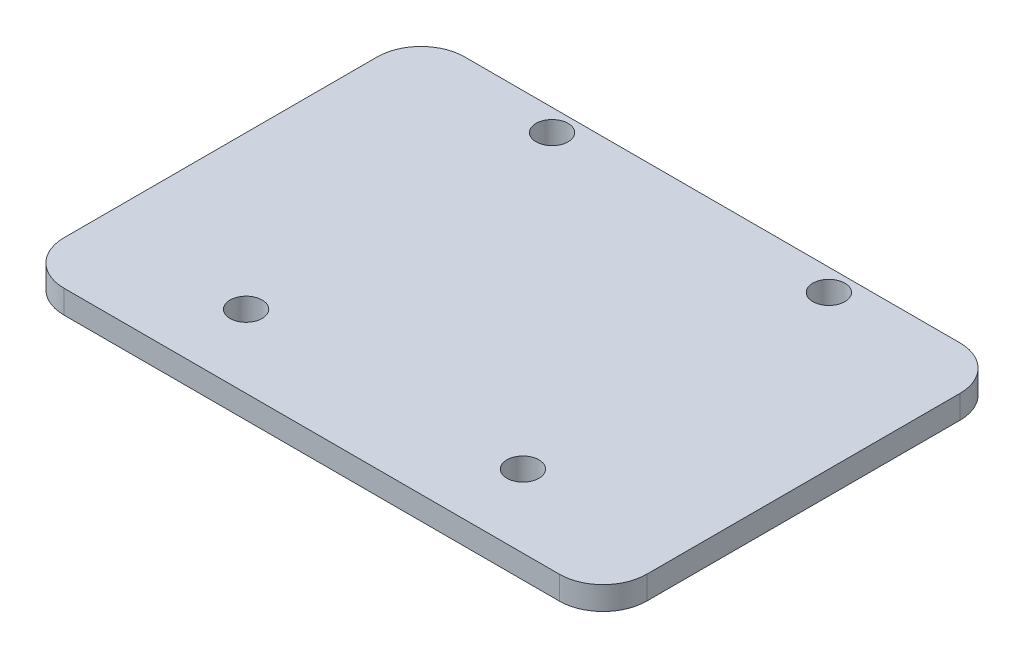
SolidWorks part; units mm, degrees
ref_plane "Front Plane" through (0, 0, 0) normal (0, 0, 1) x (1, 0, 0)
ref_plane "Top Plane" through (0, 0, 0) normal (0, 1, 0) x (1, 0, 0)
ref_plane "Right Plane" through (0, 0, 0) normal (1, 0, 0) x (0, 0, -1)
sketch "Sketch1" plane through (0, 0, 0) normal (0, 1, 0) x (1, 0, 0)
  line L0 (-20, 13.75) -> (20, -13.75) construction
  line L1 (-20, 13.75) -> (20, 13.75)
  line L2 (-20, 13.75) -> (-20, -13.75)
  line L3 (-20, -13.75) -> (20, -13.75)
  line L4 (20, 13.75) -> (20, -13.75)
  dimension "D1" = 40
  dimension "D2" = 27.5
extrude "Boss-Extrude1" add sketch "Sketch1" along normal blind 1.6
hole_wizard "M2 Clearance Hole1" positions "Sketch2" profile "Sketch3" hole size "M2" standard "ANSI Metric"
sketch "Sketch2" plane through (0, 1.6, 0) normal (0, 1, 0) x (1, 0, 0)
  line L1 (-9.5, 12.25) -> (9.5, 12.25)
  line L2 (-9.5, 12.25) -> (-9.5, -8.75)
  line L3 (-9.5, -8.75) -> (9.5, -8.75)
  line L4 (9.5, 12.25) -> (9.5, -8.75)
  line L5 (-20, -13.75) -> (20, -13.75) construction
  point P0 (-9.5, 12.25)
  point P2 (9.5, 12.25)
  point P4 (9.5, -8.75)
  point P6 (-9.5, -8.75)
  point P136 (-7.7735, 7.5486)
  point P137 (-7.7735, -7.7305)
  point P138 (7.6558, -7.7305)
  point P139 (7.6558, 7.5486)
  point P142 (0, -8.75)
  dimension "D1" = 21
  dimension "D2" = 19
  dimension "D3" = 5
sketch "Sketch3" plane through (-9.5, 1.6, -12.25) normal (1, 0, 0) x (0, 0, 1)
  line L0 (0, 0) -> (0, 5.8609)
  line L1 (0, 5.8609) -> (1.1, 5.2)
  line L2 (1.1, 5.2) -> (1.1, 0)
  line L5 (1.1, 0) -> (0, 0)
  line L10 (0, 5.8609) -> (-1.1, 5.2) construction
  line L11 (0, -6.35) -> (0, 107.95) construction
  dimension "Hole Dia." = 2.2
  dimension "Hole Depth" = 5.2
  dimension "Drill Angle" = 118
fillet "Fillet1" radius 3 4 edges at (20, 0.8, -13.75) (20, 0.8, 13.75) (-20, 0.8, 13.75) (-20, 0.8, -13.75)
